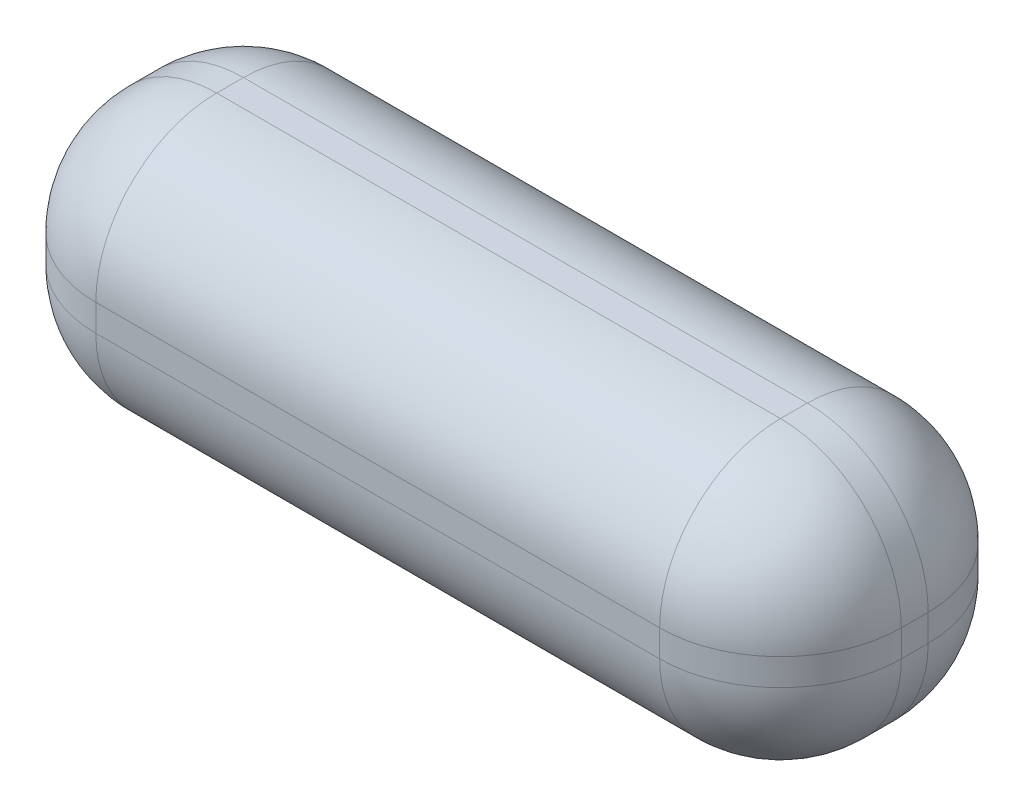
SolidWorks part; units mm, degrees
ref_plane "Front Plane" through (0, 0, 0) normal (0, 0, 1) x (1, 0, 0)
ref_plane "Top Plane" through (0, 0, 0) normal (0, 1, 0) x (1, 0, 0)
ref_plane "Right Plane" through (0, 0, 0) normal (1, 0, 0) x (0, 0, -1)
sketch "Sketch1" plane through (0, 0, 0) normal (0, 0, 1) x (1, 0, 0)
  line L1 (150, -50) -> (-150, -50)
  line L2 (150, -50) -> (150, 50)
  line L3 (150, 50) -> (-150, 50)
  line L4 (-150, -50) -> (-150, 50)
  line L5 (150, -50) -> (-150, 50) construction
  line L6 (150, 50) -> (-150, -50) construction
  point P0 (0, 0)
  dimension "D1" = 100
  dimension "D2" = 300
extrude "Boss-Extrude1" add sketch "Sketch1" along normal mid plane 100
fillet "Fillet1" radius 45 12 edges at (-150, -50, 0) (0, -50, -50) (-150, 0, -50) (150, -50, 0) (150, 0, -50) (150, 0, 50) (0, -50, 50) (-150, 0, 50) (150, 50, 0) (0, 50, 50) (-150, 50, 0) (0, 50, -50)
